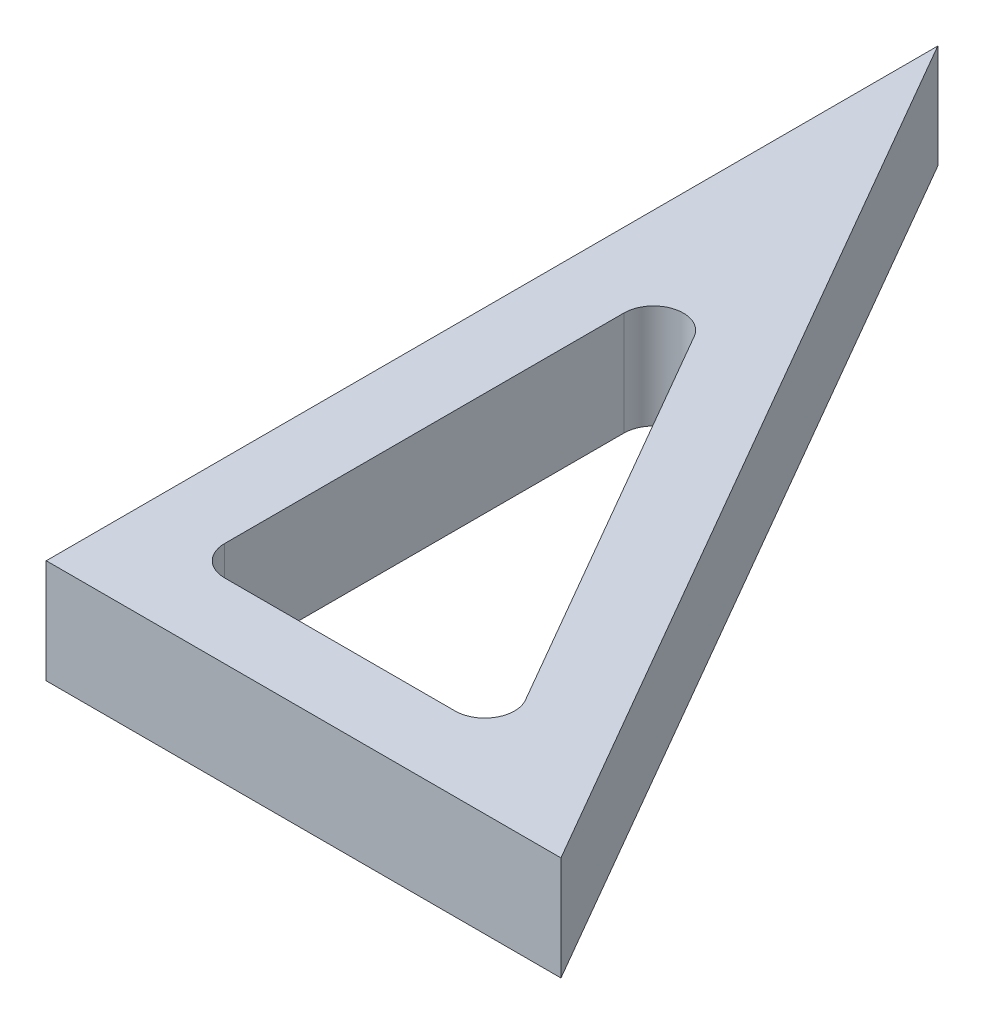
SolidWorks part; units mm, degrees
ref_plane "Front Plane" through (0, 0, 0) normal (0, 0, 1) x (1, 0, 0)
ref_plane "Top Plane" through (0, 0, 0) normal (0, 1, 0) x (1, 0, 0)
ref_plane "Right Plane" through (0, 0, 0) normal (1, 0, 0) x (0, 0, -1)
sketch "Sketch1" plane through (0, 0, 0) normal (0, 1, 0) x (1, 0, 0)
  line L0 (0, 0) -> (0, 60)
  line L1 (0, 0) -> (34.641, 0)
  line L2 (0, 60) -> (34.641, 0)
  line L3 (5, 7) -> (5, 33.8756)
  line L4 (8.7321, 34.8756) -> (24.2487, 8)
  line L5 (7, 5) -> (22.5167, 5)
  line L6 (5, 41.3397) -> (25.9808, 5) construction
  line L7 (5, 5) -> (5, 41.3397) construction
  line L8 (5, 5) -> (25.9808, 5) construction
  arc A0 (8.7321, 34.8756) -> (5, 33.8756) centre (7, 33.8756) ccw
  arc A1 (24.2487, 8) -> (22.5167, 5) centre (22.5167, 7) cw
  arc A2 (5, 7) -> (7, 5) centre (7, 7) ccw
  dimension "D4" = 2
  dimension "D1" = 60
  dimension "D2" = 60
  dimension "D3" = 5
extrude "Boss-Extrude1" add sketch "Sketch1" along normal blind 7
